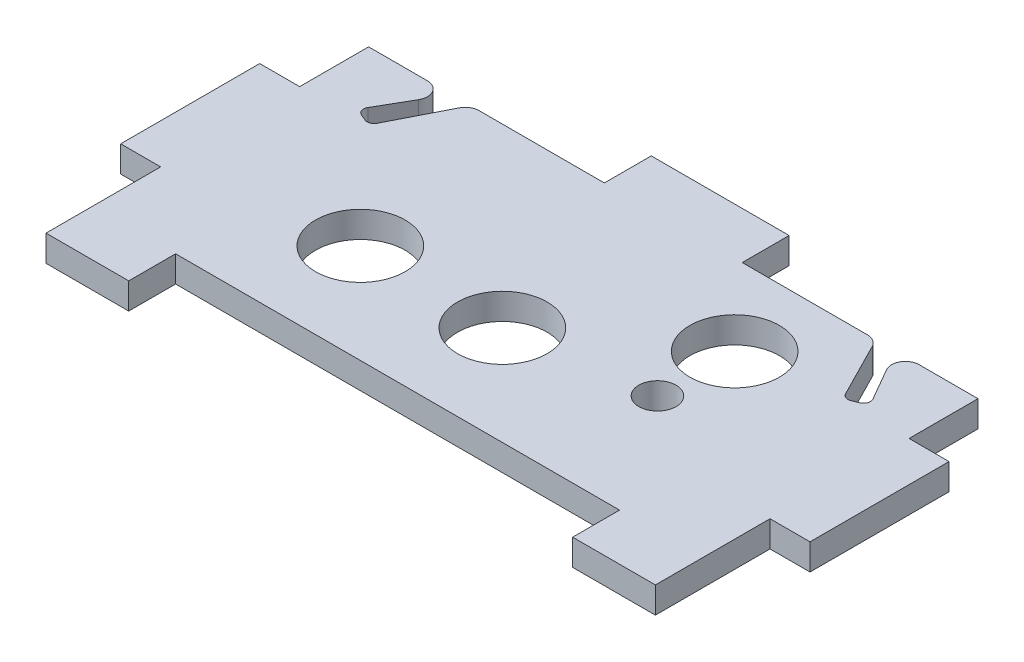
SolidWorks part; units mm, degrees
ref_plane "Front Plane" through (0, 0, 0) normal (0, 0, 1) x (1, 0, 0)
ref_plane "Top Plane" through (0, 0, 0) normal (0, 1, 0) x (1, 0, 0)
ref_plane "Right Plane" through (0, 0, 0) normal (1, 0, 0) x (0, 0, -1)
sketch "Sketch1" plane through (0, 0, 0) normal (0, 1, 0) x (1, 0, 0)
  line L0 (0, 29.083) -> (0, -47.5431) construction
  line L1 (-56.134, 29.083) -> (-40.894, 29.083)
  line L2 (-56.134, 29.083) -> (-56.134, 16.383)
  line L3 (-40.894, -21.717) -> (40.894, -21.717)
  line L4 (56.134, 29.083) -> (56.134, 16.383)
  line L5 (-56.134, 29.083) -> (56.134, -29.083) construction
  line L6 (-56.134, -29.083) -> (56.134, 29.083) construction
  line L7 (-56.134, 16.383) -> (-63.5, 16.383)
  line L9 (-56.134, -9.2306) -> (-63.5, -9.2306)
  line L10 (-63.5, 16.383) -> (-63.5, -9.2306)
  line L11 (56.134, -9.2306) -> (63.5, -9.2306)
  line L12 (63.5, 16.383) -> (63.5, -9.2306)
  line L13 (56.134, 16.383) -> (63.5, 16.383)
  line L14 (-56.134, -9.2306) -> (-56.134, -29.083)
  line L15 (56.134, -9.2306) -> (56.134, -29.083)
  line L16 (40.894, -21.717) -> (40.894, -30.353)
  line L18 (-56.134, -29.083) -> (-56.134, -30.353)
  line L19 (-56.134, -30.353) -> (-40.894, -30.353)
  line L20 (-40.894, -21.717) -> (-40.894, -30.353)
  line L21 (56.134, -30.353) -> (40.894, -30.353)
  line L22 (56.134, -29.083) -> (56.134, -30.353)
  line L23 (-37.338, 29.083) -> (-12.7, 29.083)
  line L29 (-40.894, 29.083) -> (-47.2419, 18.0833)
  line L30 (-47.2419, 18.0833) -> (-43.6859, 16.6246)
  line L31 (-37.338, 29.083) -> (-43.6859, 16.6246)
  line L32 (47.2419, 18.0833) -> (43.6859, 16.6246)
  line L33 (37.338, 29.083) -> (43.6859, 16.6246)
  line L34 (40.894, 29.083) -> (47.2419, 18.0833)
  line L35 (40.894, 29.083) -> (56.134, 29.083)
  line L36 (0, 37.719) -> (0, 26.6468) construction
  line L38 (-12.7, 29.083) -> (-12.7, 37.719)
  line L39 (-12.7, 37.719) -> (12.7, 37.719)
  line L40 (12.7, 29.083) -> (12.7, 37.719)
  line L41 (12.7, 29.083) -> (37.338, 29.083)
  point P0 (0, 0)
  dimension "D1" = 112.268
  dimension "D2" = 50.8
  dimension "D3" = 7.366
  dimension "D4" = 12.7
  dimension "D5" = 8.636
  dimension "D6" = 15.24
  dimension "D7" = 3.556
  dimension "D8" = 3.556
  dimension "D9" = 117
  dimension "D10" = 15.24
  dimension "D11" = 12.7
  dimension "D12" = 25.4
  dimension "D13" = 8.636
extrude "Boss-Extrude1" add sketch "Sketch1" along normal blind 4.826
fillet "Fillet1" radius 1.27 4 edges at (47.2419, 2.413, -18.0833) (43.6859, 2.413, -16.6246) (-43.6859, 2.413, -16.6246) (-47.2419, 2.413, -18.0833)
sketch "Sketch2" plane through (0, 4.826, 0) normal (0, 1, 0) x (1, 0, 0)
  line L0 (0, 37.719) -> (0, -42.0906) construction
  line L1 (12.7, 37.719) -> (-12.7, 37.719) construction
  line L2 (37.338, 29.083) -> (12.7, 29.083) construction
  line L5 (26.162, 14.224) -> (26.162, -9.8306) construction
  line L7 (-40.894, -21.717) -> (40.894, -21.717) construction
  circle A0 centre (26.162, 14.224) radius 8.255
  circle A1 centre (26.162, 0) radius 3.429
  circle A2 centre (-25.146, -3.429) radius 8.255
  circle A3 centre (1.016, -3.429) radius 8.255
  dimension "D1" = 16.51
  dimension "D2" = 14.859
  dimension "D3" = 26.162
  dimension "D4" = 6.858
  dimension "D5" = 14.224
  dimension "D6" = 25.146
  dimension "D7" = 18.288
  dimension "D8" = 16.51
  dimension "D9" = 16.51
  dimension "D10" = 26.162
  dimension "D11" = 18.288
extrude "Cut-Extrude1" cut sketch "Sketch2" against normal through all
fillet "Fillet2" radius 2.54 4 edges at (37.338, 2.413, -29.083) (40.894, 2.413, -29.083) (-37.338, 2.413, -29.083) (-40.894, 2.413, -29.083)
